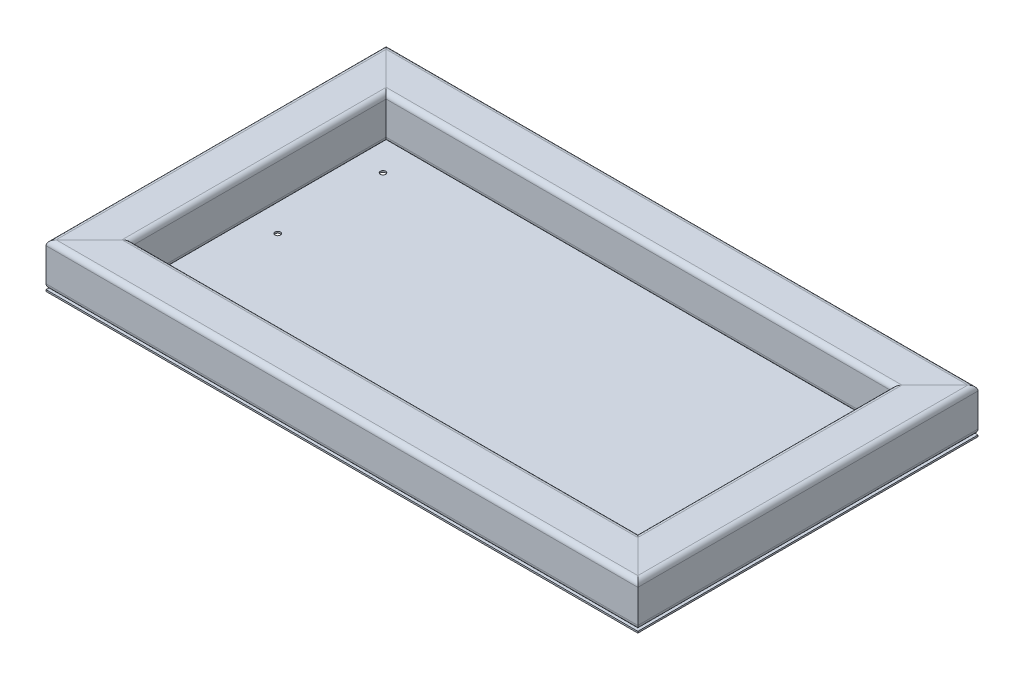
SolidWorks part; units mm, degrees
material "ASTM A36 Acero"
ref_plane "Alzado" through (0, 0, 0) normal (0, 0, 1) x (1, 0, 0)
ref_plane "Planta" through (0, 0, 0) normal (0, 1, 0) x (1, 0, 0)
ref_plane "Vista lateral" through (0, 0, 0) normal (1, 0, 0) x (0, 0, -1)
sketch "Croquis1" plane through (0, 0, 0) normal (0, 1, 0) x (1, 0, 0)
  line L1 (-348.5, 200.3) -> (348.5, 200.3)
  line L2 (-348.5, 200.3) -> (-348.5, -200.3)
  line L3 (-348.5, -200.3) -> (348.5, -200.3)
  line L4 (348.5, 200.3) -> (348.5, -200.3)
  line L5 (-348.5, 200.3) -> (348.5, -200.3) construction
  line L6 (-348.5, -200.3) -> (348.5, 200.3) construction
  point P0 (0, 0)
  dimension "D1" = 400.6
  dimension "D2" = 697
other "Tubo cuadrado 2 X 2 X 0.25(1)"
ref_plane "Plano1" through (-323.1, 25.4, -200.3) normal (0, 0, 1) x (1, 0, 0)
sketch "Sketch1" plane through (-323.1, 25.4, -200.3) normal (0, 0, 1) x (1, 0, 0)
  line L0 (-19.4, -22.4) -> (19.4, -22.4)
  line L1 (-22.4, -19.4) -> (-22.4, 19.4)
  line L2 (19.4, 22.4) -> (-19.4, 22.4)
  line L3 (22.4, 19.4) -> (22.4, -19.4)
  line L4 (-19.4, -25.4) -> (19.4, -25.4)
  line L5 (-25.4, -19.4) -> (-25.4, 19.4)
  line L6 (19.4, 25.4) -> (-19.4, 25.4)
  line L7 (25.4, 19.4) -> (25.4, -19.4)
  line L8 (0, 0) -> (22.4, 0) construction
  line L9 (0, 0) -> (0, 22.4) construction
  arc A0 (25.4, 19.4) -> (19.4, 25.4) centre (19.4, 19.4) ccw
  arc A1 (19.4, -25.4) -> (25.4, -19.4) centre (19.4, -19.4) ccw
  arc A2 (-25.4, -19.4) -> (-19.4, -25.4) centre (-19.4, -19.4) ccw
  arc A3 (-19.4, 25.4) -> (-25.4, 19.4) centre (-19.4, 19.4) ccw
  arc A4 (-19.4, 22.4) -> (-22.4, 19.4) centre (-19.4, 19.4) ccw
  arc A5 (22.4, 19.4) -> (19.4, 22.4) centre (19.4, 19.4) ccw
  arc A6 (19.4, -22.4) -> (22.4, -19.4) centre (19.4, -19.4) ccw
  arc A7 (-22.4, -19.4) -> (-19.4, -22.4) centre (-19.4, -19.4) ccw
  point P3 (0, 25.4)
  point P4 (25.4, 0)
  point P5 (0, -25.4)
  point P6 (-25.4, 0)
  point P7 (-25.4, 25.4)
  point P8 (-25.4, -25.4)
  point P33 (0, 0)
  point P35 (25.4, -25.4)
  point P36 (25.4, 25.4)
  point P37 (0, 0)
  dimension "D1" = 6
  dimension "Thickness" = 3
  dimension "V_leg" = 50.8
sketch "Croquis3" plane through (0, 0, 0) normal (0, -1, 0) x (1, 0, 0)
  line L0 (348.5, -200.3) -> (342.5, -194.3) construction
  line L1 (-348.5, 200.3) -> (348.5, 200.3)
  line L2 (-348.5, 200.3) -> (-348.5, -200.3)
  line L3 (-348.5, -200.3) -> (348.5, -200.3)
  line L4 (348.5, 200.3) -> (348.5, -200.3)
  line L5 (-348.5, 200.3) -> (348.5, -200.3) construction
  line L6 (-348.5, -200.3) -> (348.5, 200.3) construction
  line L7 (-348.5, -200.3) -> (348.5, -200.3) construction
  point P0 (0, 0)
extrude "Saliente-Extruir1" add sketch "Croquis3" along normal blind 1.9 separate body
sketch "Croquis4" plane through (0, 0, 0) normal (0, 1, 0) x (1, 0, 0)
  circle A0 centre (-269.2, 117.3) radius 3.175
  circle A1 centre (-269.2, -6.7) radius 3.175
  circle A2 centre (269.2, 117.3) radius 3.175
  circle A3 centre (269.2, -6.7) radius 3.175
extrude "Cortar-Extruir1" cut sketch "Croquis4" against normal blind 10
